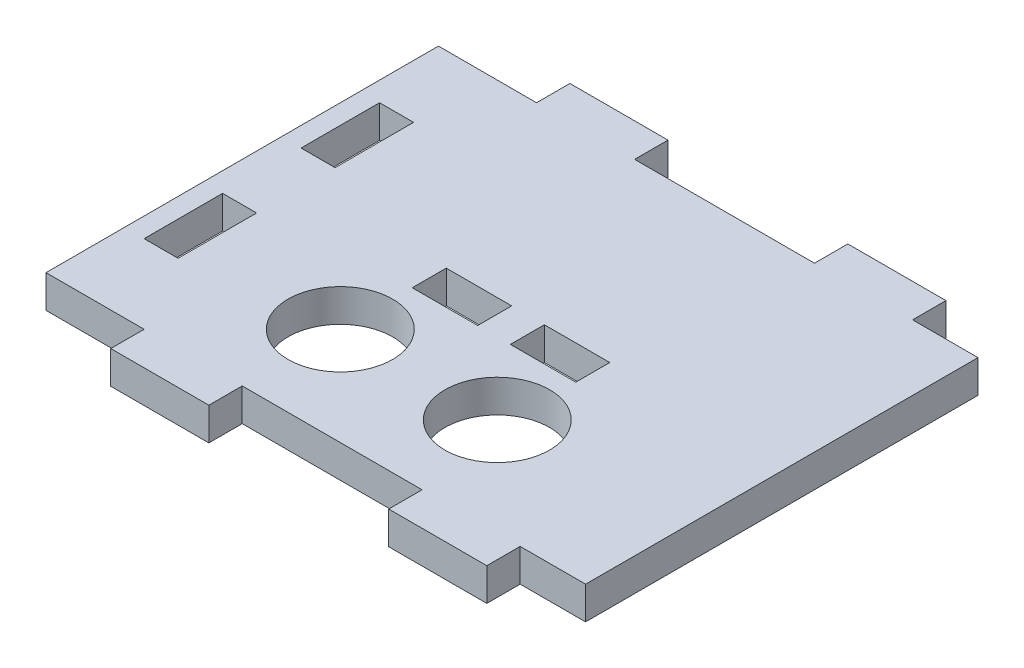
SolidWorks part; units mm, degrees
ref_plane "Front Plane" through (0, 0, 0) normal (0, 0, 1) x (1, 0, 0)
ref_plane "Top Plane" through (0, 0, 0) normal (0, 1, 0) x (1, 0, 0)
ref_plane "Right Plane" through (0, 0, 0) normal (1, 0, 0) x (0, 0, -1)
sketch "Sketch1" plane through (0, 0, 0) normal (0, 1, 0) x (1, 0, 0)
  line L0 (25, 30) -> (25, -30)
  line L1 (25, -30) -> (15, -30)
  line L2 (15, -30) -> (15, -35.1)
  line L3 (15, -35.1) -> (0, -35.1)
  line L4 (0, -35.1) -> (0, -30)
  line L5 (0, -30) -> (-27.5, -30)
  line L6 (-27.5, -30) -> (-27.5, -35.1)
  line L7 (-27.5, -35.1) -> (-42.5, -35.1)
  line L8 (-42.5, -35.1) -> (-42.5, -30)
  line L9 (-42.5, -30) -> (-57.5, -30)
  line L10 (-57.5, -30) -> (-57.5, 30)
  line L22 (-27.5, 1.2) -> (-17.5, 1.2)
  line L23 (-27.5, 1.2) -> (-27.5, -4)
  line L24 (-27.5, -4) -> (-17.5, -4)
  line L25 (-17.5, 1.2) -> (-17.5, -4)
  line L26 (-27.5, 1.2) -> (-17.5, -4) construction
  line L27 (-27.5, -4) -> (-17.5, 1.2) construction
  line L28 (-12.5, 1.2) -> (-2.5, 1.2)
  line L29 (-12.5, 1.2) -> (-12.5, -4)
  line L30 (-12.5, -4) -> (-2.5, -4)
  line L31 (-2.5, 1.2) -> (-2.5, -4)
  line L32 (-12.5, 1.2) -> (-2.5, -4) construction
  line L33 (-12.5, -4) -> (-2.5, 1.2) construction
  line L34 (25, 30) -> (15, 30)
  line L35 (15, 30) -> (15, 35.1)
  line L36 (15, 35.1) -> (0, 35.1)
  line L37 (0, 35.1) -> (0, 30)
  line L38 (0, 30) -> (-27.5, 30)
  line L39 (-27.5, 30) -> (-27.5, 35.1)
  line L40 (-27.5, 35.1) -> (-42.5, 35.1)
  line L41 (-42.5, 35.1) -> (-42.5, 30)
  line L42 (-42.5, 30) -> (-57.5, 30)
  line L44 (-54.5, -6) -> (-49.3, -6)
  line L45 (-54.5, -6) -> (-54.5, -18)
  line L46 (-54.5, -18) -> (-49.3, -18)
  line L47 (-49.3, -6) -> (-49.3, -18)
  line L48 (-54.5, -6) -> (-49.3, -18) construction
  line L49 (-54.5, -18) -> (-49.3, -6) construction
  line L50 (-54.5, 18) -> (-49.3, 18)
  line L51 (-49.3, 6) -> (-49.3, 18)
  line L52 (-54.5, 6) -> (-49.3, 6)
  line L53 (-54.5, 6) -> (-54.5, 18)
  circle A0 centre (-27.5, -15) radius 8
  circle A1 centre (-3.5, -15) radius 8
  point P0 (-22.5, -1.4)
  point P26 (-7.5, -1.4)
  dimension "D34" = 15
  dimension "D36" = 24
  dimension "D2" = 10
  dimension "D3" = 15
  dimension "D4" = 27.5
  dimension "D5" = 15
  dimension "D6" = 15
  dimension "D7" = 5.1
  dimension "D8" = 5.1
  dimension "D9" = 5.1
  dimension "D10" = 5.1
  dimension "D11" = 10
  dimension "D12" = 10
  dimension "D13" = 5.2
  dimension "D14" = 5.2
  dimension "D15" = 15
  dimension "D16" = 30
  dimension "D17" = 26
  dimension "D18" = 60
  dimension "D19" = 15
  dimension "D20" = 5.1
  dimension "D21" = 15
  dimension "D22" = 5.1
  dimension "D23" = 27.5
  dimension "D24" = 15
  dimension "D25" = 5.1
  dimension "D26" = 10
  dimension "D27" = 5.1
  dimension "D28" = 12
  dimension "D29" = 12
  dimension "D30" = 5.2
  dimension "D31" = 12
  dimension "D32" = 3
  dimension "D33" = 12
  dimension "D35" = 30
extrude "Boss-Extrude1" add sketch "Sketch1" along normal blind 5
